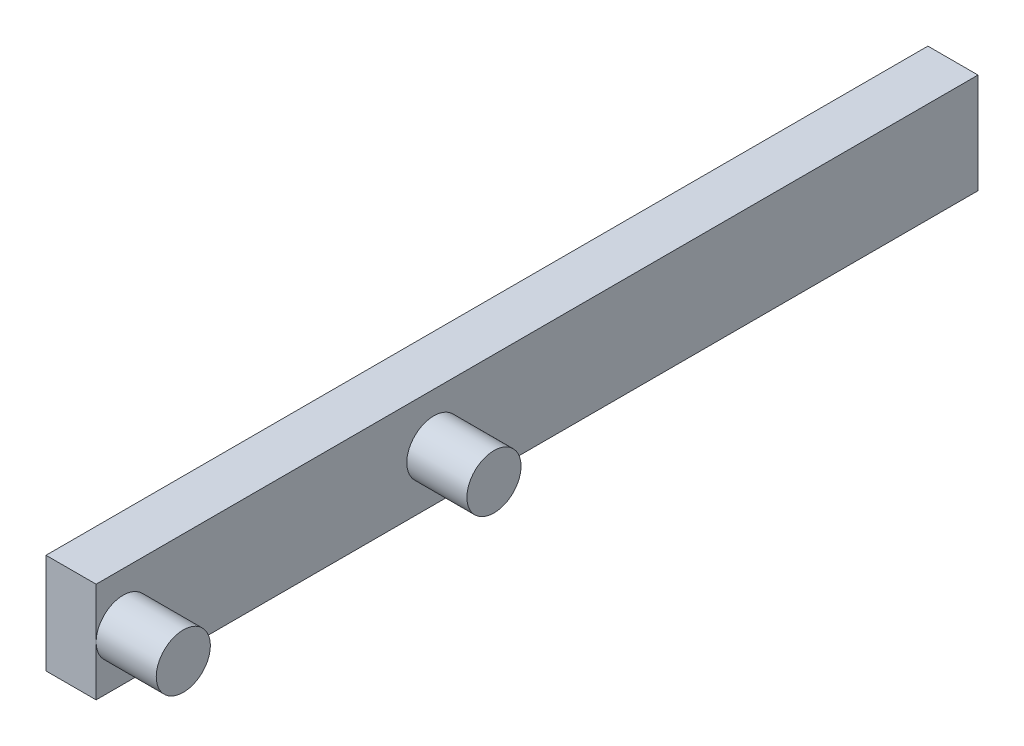
SolidWorks part; units mm, degrees
ref_plane "Front Plane" through (0, 0, 0) normal (0, 0, 1) x (1, 0, 0)
ref_plane "Top Plane" through (0, 0, 0) normal (0, 1, 0) x (1, 0, 0)
ref_plane "Right Plane" through (0, 0, 0) normal (1, 0, 0) x (0, 0, -1)
sketch "Sketch1" plane through (0, 0, 0) normal (1, 0, 0) x (0, 0, -1)
  line L1 (22, -2.5) -> (-22, -2.5)
  line L2 (22, -2.5) -> (22, 2.5)
  line L3 (22, 2.5) -> (-22, 2.5)
  line L4 (-22, -2.5) -> (-22, 2.5)
  line L5 (22, -2.5) -> (-22, 2.5) construction
  line L6 (22, 2.5) -> (-22, -2.5) construction
  point P0 (0, 0)
  dimension "D1" = 44
  dimension "D2" = 5
extrude "Boss-Extrude1" add sketch "Sketch1" along normal blind 2.5
sketch "Sketch2" plane through (2.5, 0, 0) normal (1, 0, 0) x (0, 0, -1)
  line L0 (-22, 0) -> (22, 0) construction
  line L1 (-22, 2.5) -> (-22, -2.5) construction
  line L2 (22, -2.5) -> (22, 2.5) construction
  circle A0 centre (-20.65, 0) radius 1.35
  circle A1 centre (-5.15, 0) radius 1.35
  dimension "D1" = 2.7
  dimension "D2" = 15.5
extrude "Boss-Extrude2" add sketch "Sketch2" along normal blind 3
